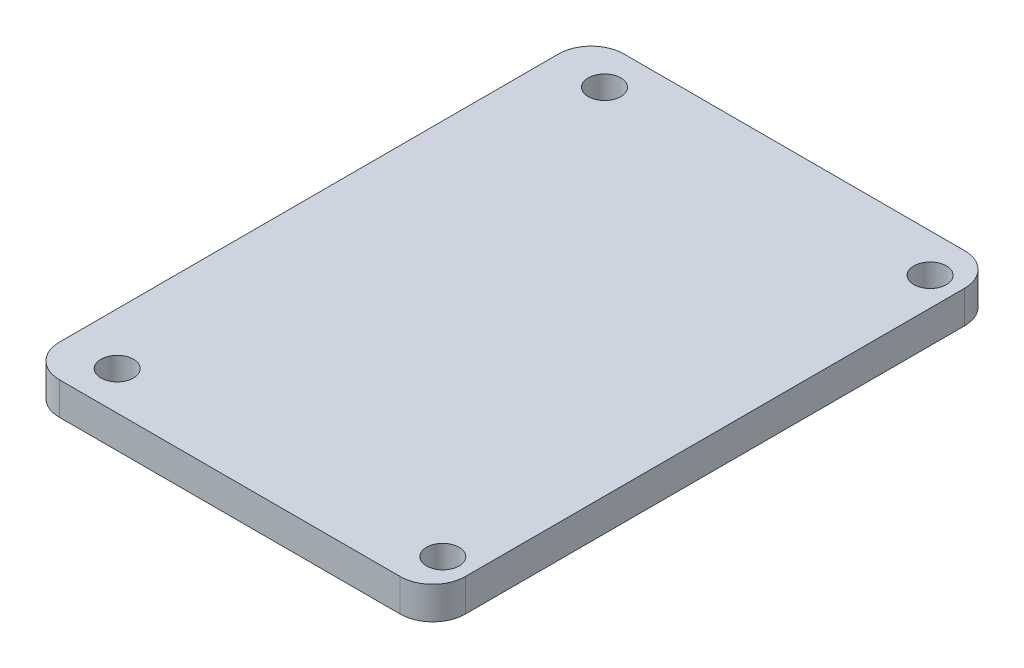
SolidWorks part; units mm, degrees
ref_plane "Front Plane" through (0, 0, 0) normal (0, 0, 1) x (1, 0, 0)
ref_plane "Top Plane" through (0, 0, 0) normal (0, 1, 0) x (1, 0, 0)
ref_plane "Right Plane" through (0, 0, 0) normal (1, 0, 0) x (0, 0, -1)
sketch "Sketch2" plane through (0, 0, 0) normal (0, 1, 0) x (1, 0, 0)
  line L1 (-37.5, -26) -> (27.5, -26)
  line L2 (-37.5, -26) -> (-37.5, 26)
  line L3 (-37.5, 26) -> (27.5, 26)
  line L4 (27.5, -26) -> (27.5, 26)
  line L5 (0, 27) -> (0, -27) construction
  line L6 (-32.5, 0) -> (32.5, 0) construction
  line L7 (-24.875, -22.45) -> (24.875, -22.45)
  line L8 (-24.875, -22.45) -> (-24.875, 22.45)
  line L9 (-24.875, 22.45) -> (24.875, 22.45)
  line L10 (24.875, -22.45) -> (24.875, 22.45)
  line L11 (0, 22.45) -> (0, -22.45) construction
  line L12 (-24.875, 0) -> (24.875, 0) construction
  circle A0 centre (-24.875, 22.45) radius 1.5
  circle A1 centre (24.875, 22.45) radius 1.5
  circle A2 centre (24.875, -22.45) radius 1.5
  circle A3 centre (-24.875, -22.45) radius 1.5
  point P0 (0, 0)
  point P4 (0, 0)
  dimension "D5" = 3
  dimension "D1" = 52
  dimension "D2" = 65
  dimension "D3" = 44.9
  dimension "D4" = 49.75
  dimension "D8" = 3.55
  dimension "D9" = 2.625
  dimension "D6" = 2
  dimension "D7" = 2
extrude "Boss-Extrude1" add sketch "Sketch2" along normal blind 3 contours L1 L4 L3 L2 A3 L8 A0 L9 A1 L10 A2 L7 | A3 L7 A2 L10 A1 L9 A0 L8
fillet "Fillet1" radius 3 4 edges at (27.5, 1.5, 26) (-37.5, 1.5, 26) (27.5, 1.5, -26) (-37.5, 1.5, -26)
sketch "Sketch3" plane through (0, 3, 0) normal (0, 1, 0) x (1, 0, 0)
  circle A0 centre (24.875, 22.45) radius 1.5
  circle A1 centre (-5.125, 22.45) radius 1.5
  circle A2 centre (-5.125, -22.45) radius 1.5
  circle A3 centre (24.875, -22.45) radius 1.5
  dimension "D1" = 3
  dimension "D2" = 2
  dimension "D3" = 2
extrude "Cut-Extrude1" cut sketch "Sketch3" against normal blind 10
sketch "Sketch4" plane through (0, 3, 0) normal (0, 1, 0) x (1, 0, 0)
  line L0 (27.5, 0) -> (-9.9, 0)
  line L1 (-9.9, 0) -> (-9.9, 26)
  line L3 (-9.9, 26) -> (-43.0616, 26)
  line L4 (-9.9, 26) -> (-9.9, -28.6609)
  line L5 (-9.9, -28.6609) -> (-43.0616, -28.6609)
  line L6 (-43.0616, 26) -> (-43.0616, -28.6609)
  circle M3 centre (-24.875, 22.45) radius 1.5
  circle M5 centre (-24.875, -22.45) radius 1.5
  line M7 (-34.5, -26) -> (24.5, -26)
  line M11 (24.5, 26) -> (-34.5, 26)
  arc M12 (-34.5, 26) -> (-37.5, 23) centre (-34.5, 23) ccw
  line M13 (-37.5, 23) -> (-37.5, -23)
  arc M14 (-37.5, -23) -> (-34.5, -26) centre (-34.5, -23) ccw
  dimension "D1" = 37.4
extrude "Cut-Extrude2" cut sketch "Sketch4" against normal blind 10 contours L4 L1 M11 M12 M13 M14 M7 M3 M5
fillet "Fillet2" radius 3 2 edges at (-9.9, 1.5, 26) (-9.9, 1.5, -26)
